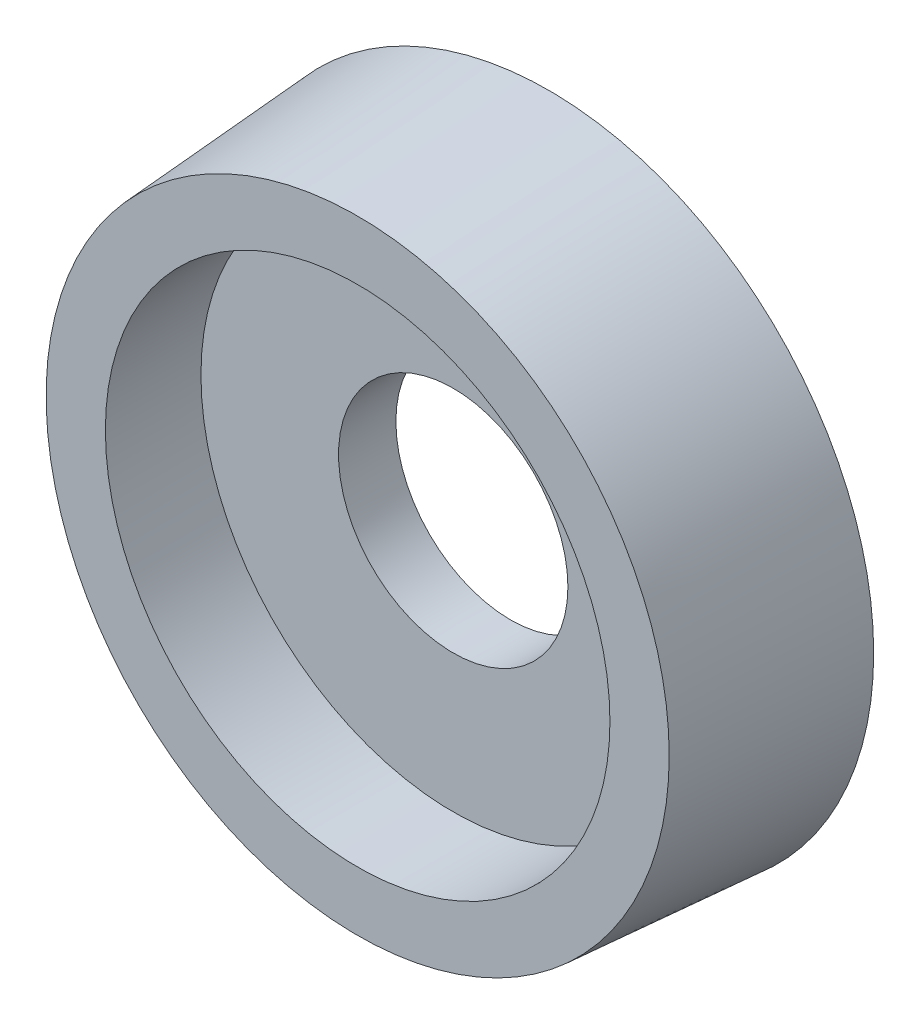
SolidWorks part; units mm, degrees
ref_plane "Спереди" through (0, 0, 0) normal (0, 0, 1) x (1, 0, 0)
ref_plane "Сверху" through (0, 0, 0) normal (0, 1, 0) x (1, 0, 0)
ref_plane "Справа" through (0, 0, 0) normal (1, 0, 0) x (0, 0, -1)
sketch "Эскиз1" plane through (0, 0, 0) normal (0, 0, 1) x (1, 0, 0)
  circle A0 centre (0, 0) radius 8.5
  dimension "D1" = 17
extrude "Бобышка-Вытянуть1" add sketch "Эскиз1" along normal blind 5 draft 4 contours A0
sketch "Эскиз3" plane through (0, 0, 0) normal (0, 0, -1) x (-1, 0, 0)
  circle A0 centre (0, 0) radius 5
  dimension "D1" = 10
extrude "Вырез-Вытянуть1" cut sketch "Эскиз3" against normal blind 1
sketch "Эскиз4" plane through (0, 0, 5) normal (0, 0, 1) x (1, 0, 0)
  circle A0 centre (0, 0) radius 6.6
  dimension "D1" = 13.2
extrude "Вырез-Вытянуть2" cut sketch "Эскиз4" against normal blind 2.5
sketch "Эскиз5" plane through (0, 0, 2.5) normal (0, 0, 1) x (1, 0, 0)
  circle A0 centre (0, 0) radius 3
  dimension "D1" = 6
extrude "Вырез-Вытянуть3" cut sketch "Эскиз5" against normal through all both and the other way through all
